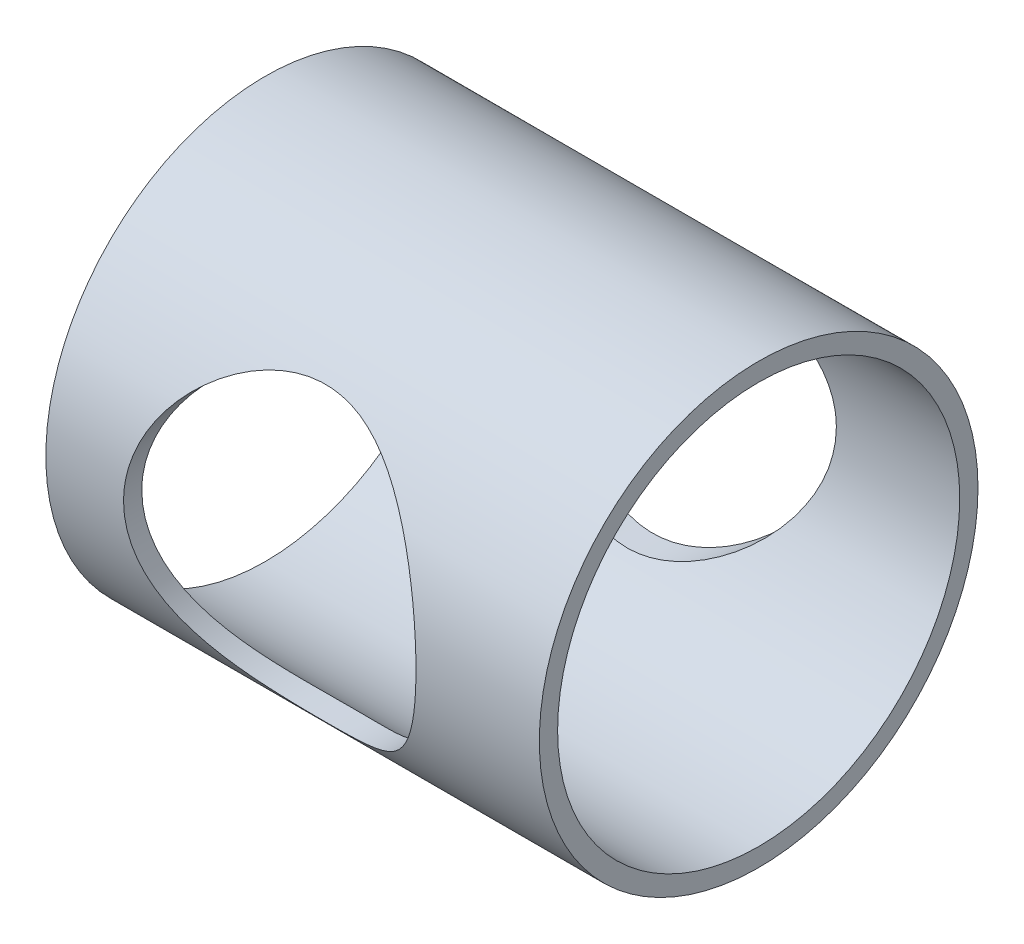
SolidWorks part; units mm, degrees
material "6061-T6 (SS)"
ref_plane "Front Plane" through (0, 0, 0) normal (0, 0, 1) x (1, 0, 0)
ref_plane "Top Plane" through (0, 0, 0) normal (0, 1, 0) x (1, 0, 0)
ref_plane "Right Plane" through (0, 0, 0) normal (1, 0, 0) x (0, 0, -1)
sketch "Sketch1" plane through (0, 0, 0) normal (1, 0, 0) x (0, 0, -1)
  circle A0 centre (0, 0) radius 38.1
  dimension "D1" = 76.2
extrude "Boss-Extrude1" add sketch "Sketch1" along normal mid plane 85.725
shell "Shell1" thickness 3.175
sketch "Sketch2" plane through (0, 0, 0) normal (0, 0, 1) x (1, 0, 0)
  line L0 (-42.8625, 38.1) -> (-42.8625, -38.1) construction
  line L1 (42.8625, -38.1) -> (42.8625, 38.1) construction
  line L2 (-42.8625, 0) -> (42.8625, 0) construction
  circle A0 centre (-3.9688, 0) radius 25.4
  dimension "D1" = 50.8
  dimension "D2" = 46.8312
extrude "Cut-Extrude1" cut sketch "Sketch2" along normal through all both and the other way through all
